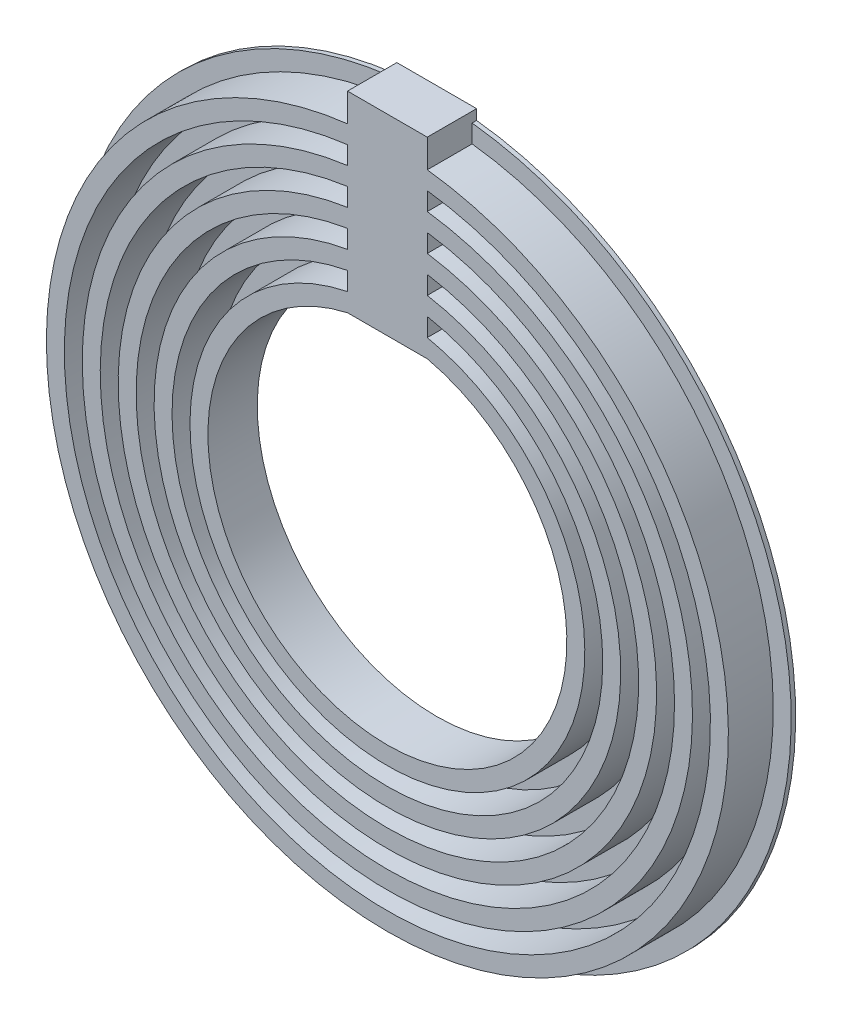
SolidWorks part; units mm, degrees
ref_plane "Alzado" through (0, 0, 0) normal (0, 0, 1) x (1, 0, 0)
ref_plane "Planta" through (0, 0, 0) normal (0, 1, 0) x (1, 0, 0)
ref_plane "Vista lateral" through (0, 0, 0) normal (1, 0, 0) x (0, 0, -1)
sketch "Croquis1" plane through (0, 0, 0) normal (0, 0, 1) x (1, 0, 0)
  circle A0 centre (0, 0) radius 20
  circle A1 centre (0, 0) radius 10
  dimension "D1" = 40
  dimension "D2" = 20
extrude "Saliente-Extruir1" add sketch "Croquis1" along normal blind 2.75
sketch "Croquis2" plane through (0, 0, 2.75) normal (0, 0, 1) x (1, 0, 0)
  circle A0 centre (0, 0) radius 10
  circle A1 centre (0, 0) radius 11
  circle A2 centre (0, 0) radius 12
  circle A3 centre (0, 0) radius 13
  circle A4 centre (0, 0) radius 14
  circle A5 centre (0, 0) radius 15
  circle A6 centre (0, 0) radius 16
  circle A7 centre (0, 0) radius 17
  circle A8 centre (0, 0) radius 18
  circle A9 centre (0, 0) radius 19
  circle A10 centre (0, 0) radius 20
  circle A11 centre (0, 0) radius 21
extrude "Cortar-Extruir1" cut sketch "Croquis2" against normal blind 2.5 contours A2 A1 | A4 A3 | A6 A5 | A8 A7 | A10 A9
sketch "Croquis3" plane through (0, 0, 2.75) normal (0, 0, 1) x (1, 0, 0)
  line L0 (0, 10) -> (0, 9.75)
  line L1 (0, 9.75) -> (-2.222, 9.75)
  line L2 (-2.222, 9.75) -> (2.222, 9.75)
  line L3 (2.222, 9.75) -> (2.222, 20.4467)
  line L4 (2.222, 20.4467) -> (-2.222, 20.4467)
  line L5 (-2.222, 20.4467) -> (-2.222, 9.75)
  circle A0 centre (0, 0) radius 10 construction
  dimension "D1" = 0.25
extrude "Saliente-Extruir2" add sketch "Croquis3" against normal blind 2.75
